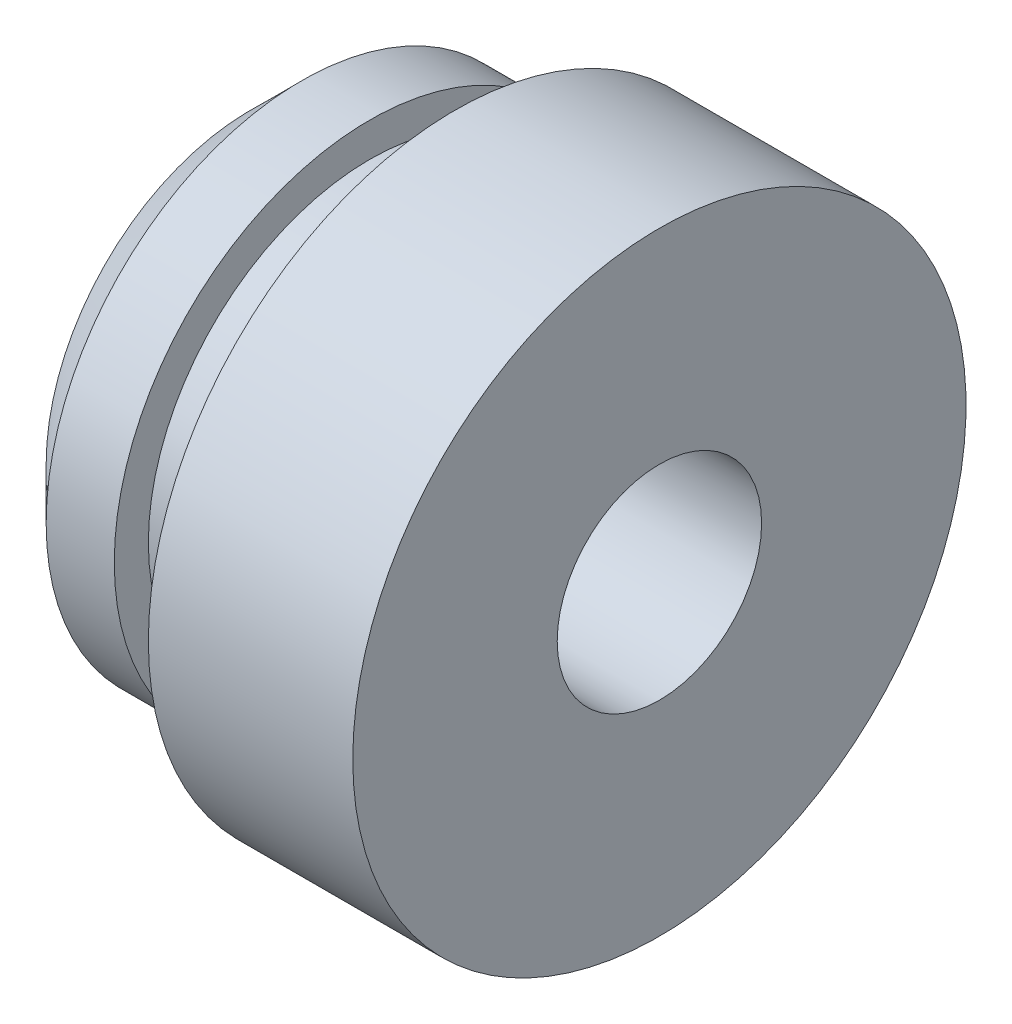
SolidWorks part; units mm, degrees
ref_plane "前视基准面" through (0, 0, 0) normal (0, 0, 1) x (1, 0, 0)
ref_plane "上视基准面" through (0, 0, 0) normal (0, 1, 0) x (1, 0, 0)
ref_plane "右视基准面" through (0, 0, 0) normal (1, 0, 0) x (0, 0, -1)
sketch "草图1" plane through (0, 0, 0) normal (0, 0, 1) x (1, 0, 0)
  line L0 (1295.2037, 982.831) -> (1295.2037, 979.831)
  line L1 (1295.2037, 982.831) -> (1302.8037, 982.831)
  line L2 (1292.3037, 987.331) -> (1294.3037, 987.331)
  line L3 (1296.8037, 988.831) -> (1302.8037, 988.831)
  line L4 (1294.3037, 986.331) -> (1296.8037, 986.331)
  line L5 (1295.2037, 979.831) -> (1290.8037, 979.831)
  line L48 (1287.3338, 979.831) -> (1306.8047, 979.831) construction
  line L51 (1302.8037, 988.831) -> (1302.8037, 982.831)
  line L52 (1290.8037, 985.831) -> (1290.8037, 979.831)
  line L55 (1296.8037, 988.831) -> (1296.8037, 986.331)
  line L56 (1294.3037, 987.331) -> (1294.3037, 986.331)
  line L61 (1290.8037, 985.831) -> (1292.3037, 987.331)
  dimension "D2" = 6.5
revolve "旋转1" add sketch "草图1" angle 360 about L48
